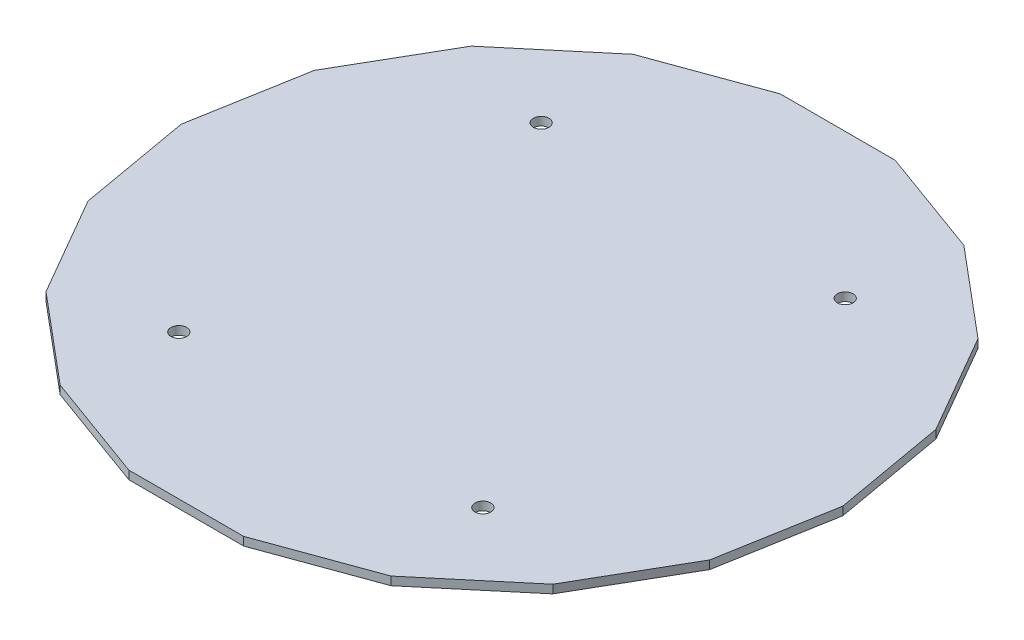
SolidWorks part; units mm, degrees
ref_plane "Front Plane" through (0, 0, 0) normal (0, 0, 1) x (1, 0, 0)
ref_plane "Top Plane" through (0, 0, 0) normal (0, 1, 0) x (1, 0, 0)
ref_plane "Right Plane" through (0, 0, 0) normal (1, 0, 0) x (0, 0, -1)
sketch "Sketch1" plane through (0, 0, 0) normal (0, 1, 0) x (1, 0, 0)
  line L1 (63, 0) -> (59.2006, 21.5473)
  line L2 (59.2006, 21.5473) -> (48.2608, 40.4956)
  line L3 (48.2608, 40.4956) -> (31.5, 54.5596)
  line L4 (31.5, 54.5596) -> (10.9398, 62.0429)
  line L5 (10.9398, 62.0429) -> (-10.9398, 62.0429)
  line L6 (-10.9398, 62.0429) -> (-31.5, 54.5596)
  line L7 (-31.5, 54.5596) -> (-48.2608, 40.4956)
  line L8 (-48.2608, 40.4956) -> (-59.2006, 21.5473)
  line L9 (-59.2006, 21.5473) -> (-63, 0)
  line L10 (-63, 0) -> (-59.2006, -21.5473)
  line L11 (-59.2006, -21.5473) -> (-48.2608, -40.4956)
  line L12 (-48.2608, -40.4956) -> (-31.5, -54.5596)
  line L13 (-31.5, -54.5596) -> (-10.9398, -62.0429)
  line L14 (-10.9398, -62.0429) -> (10.9398, -62.0429)
  line L15 (10.9398, -62.0429) -> (31.5, -54.5596)
  line L16 (31.5, -54.5596) -> (48.2608, -40.4956)
  line L17 (48.2608, -40.4956) -> (59.2006, -21.5473)
  line L18 (59.2006, -21.5473) -> (63, 0)
  circle A0 centre (0, 0) radius 62.0429 construction
  dimension "D1" = 126
extrude "Boss-Extrude1" add sketch "Sketch1" along normal blind 1.6
sketch "Sketch3" plane through (0, 1.6, 0) normal (0, 1, 0) x (1, 0, 0)
  line L1 (-30, -38) -> (30, -38) construction
  line L2 (-30, -38) -> (-30, 38) construction
  line L3 (-30, 38) -> (30, 38) construction
  line L4 (30, -38) -> (30, 38) construction
  line L5 (-30, -38) -> (30, 38) construction
  line L6 (-30, 38) -> (30, -38) construction
  circle A4 centre (-30, -38) radius 1.5
  circle A5 centre (30, -38) radius 1.5
  point P0 (0, 0)
  dimension "D3" = 3
  dimension "D1" = 76
  dimension "D2" = 60
extrude "Cut-Extrude1" [suppressed] cut sketch "Sketch3" against normal up to surface (1.6 mm away)
sketch "Sketch4" plane through (0, 1.6, 0) normal (0, 1, 0) x (1, 0, 0)
  line L1 (48, 0) -> (45.1052, 16.417) construction
  line L2 (45.1052, 16.417) -> (36.7701, 30.8538) construction
  line L3 (36.7701, 30.8538) -> (24, 41.5692) construction
  line L4 (24, 41.5692) -> (8.3351, 47.2708) construction
  line L5 (8.3351, 47.2708) -> (-8.3351, 47.2708) construction
  line L6 (-8.3351, 47.2708) -> (-24, 41.5692) construction
  line L7 (-24, 41.5692) -> (-36.7701, 30.8538) construction
  line L8 (-36.7701, 30.8538) -> (-45.1052, 16.417) construction
  line L9 (-45.1052, 16.417) -> (-48, 0) construction
  line L10 (-48, 0) -> (-45.1052, -16.417) construction
  line L11 (-45.1052, -16.417) -> (-36.7701, -30.8538) construction
  line L12 (-36.7701, -30.8538) -> (-24, -41.5692) construction
  line L13 (-24, -41.5692) -> (-8.3351, -47.2708) construction
  line L14 (-8.3351, -47.2708) -> (8.3351, -47.2708) construction
  line L15 (8.3351, -47.2708) -> (24, -41.5692) construction
  line L16 (24, -41.5692) -> (36.7701, -30.8538) construction
  line L17 (36.7701, -30.8538) -> (45.1052, -16.417) construction
  line L18 (45.1052, -16.417) -> (48, 0) construction
  circle A0 centre (0, 0) radius 47.2708 construction
  circle A1 centre (36.7701, 30.8538) radius 1.5
  circle A2 centre (-36.7701, 30.8538) radius 1.5
  circle A3 centre (36.7701, -30.8538) radius 1.5
  circle A4 centre (-36.7701, -30.8538) radius 1.5
  dimension "D2" = 3
  dimension "D1" = 96
extrude "Cut-Extrude2" [suppressed] cut sketch "Sketch4" against normal up to surface (1.6 mm away)
sketch "Sketch5" plane through (0, 1.6, 0) normal (0, 1, 0) x (1, 0, 0)
  line L1 (-17.5, -42.5) -> (17.5, -42.5) construction
  line L2 (-17.5, -42.5) -> (-17.5, 42.5) construction
  line L3 (-17.5, 42.5) -> (17.5, 42.5) construction
  line L4 (17.5, -42.5) -> (17.5, 42.5) construction
  line L5 (-17.5, -42.5) -> (17.5, 42.5) construction
  line L6 (-17.5, 42.5) -> (17.5, -42.5) construction
  circle A0 centre (-17.5, -42.5) radius 1.5
  circle A1 centre (17.5, -42.5) radius 1.5
  point P0 (0, 0)
  dimension "D3" = 3
  dimension "D1" = 85
  dimension "D2" = 35
extrude "Cut-Extrude3" [suppressed] cut sketch "Sketch5" against normal up to surface (1.6 mm away)
sketch "Sketch7" plane through (0, 1.6, 0) normal (0, 1, 0) x (1, 0, 0)
  line L0 (-39.8804, 47.5276) -> (-28.953, 34.5049) construction
  line L3 (-31.5, 54.5596) -> (-48.2608, 40.4956) construction
  line L4 (39.8804, 47.5276) -> (28.953, 34.5049) construction
  line L5 (48.2608, 40.4956) -> (31.5, 54.5596) construction
  line L7 (-28.953, -34.5049) -> (28.953, -34.5049) construction
  line L8 (-28.953, -34.5049) -> (-28.953, 34.5049) construction
  line L9 (-28.953, 34.5049) -> (28.953, 34.5049) construction
  line L10 (28.953, -34.5049) -> (28.953, 34.5049) construction
  line L11 (-28.953, -34.5049) -> (28.953, 34.5049) construction
  line L12 (-28.953, 34.5049) -> (28.953, -34.5049) construction
  circle A0 centre (-28.953, 34.5049) radius 1.5
  circle A1 centre (28.953, 34.5049) radius 1.5
  circle A2 centre (-28.953, -34.5049) radius 1.5
  circle A3 centre (28.953, -34.5049) radius 1.5
  point P11 (0, 0)
  dimension "D5" = 3
  dimension "D1" = 69.0097
  dimension "D3" = 90
  dimension "D4" = 90
  dimension "D6" = 57.906
extrude "Cut-Extrude4" cut sketch "Sketch7" against normal up to surface (1.6 mm away) up to face at (0, 0, 0)
sketch "Sketch8" plane through (0, 1.6, 0) normal (0, 1, 0) x (1, 0, 0)
